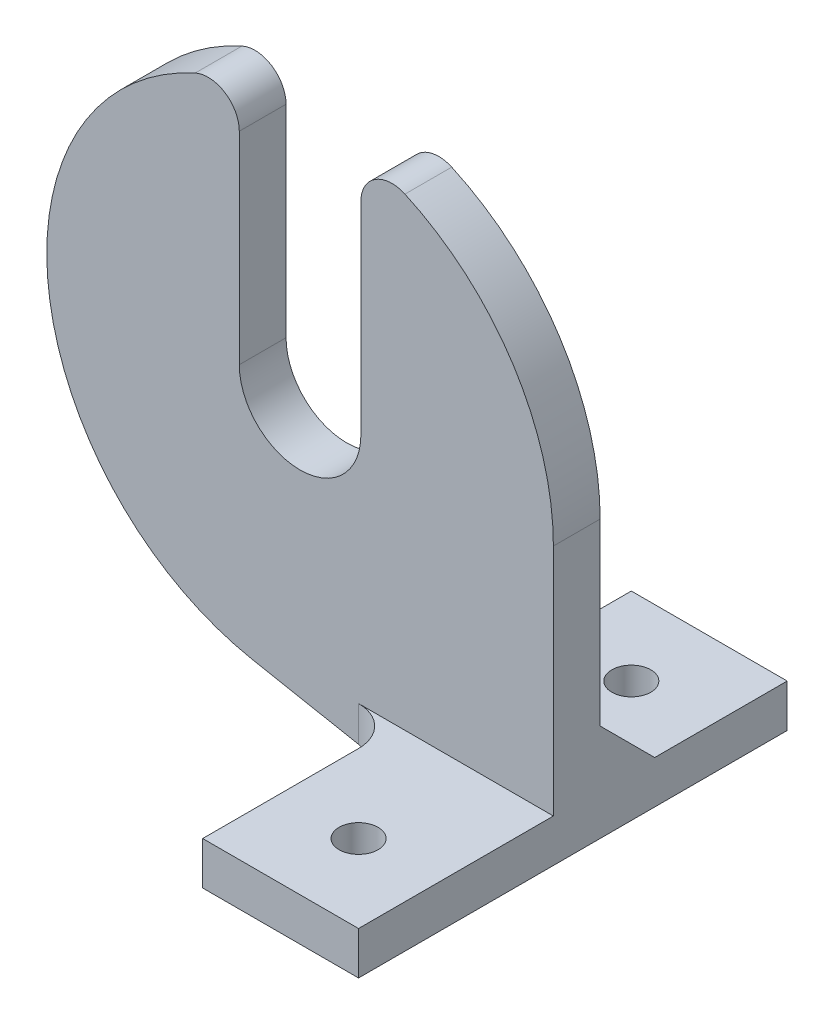
SolidWorks part; units mm, degrees
ref_plane "Front Plane" through (0, 0, 0) normal (0, 0, 1) x (1, 0, 0)
ref_plane "Top Plane" through (0, 0, 0) normal (0, 1, 0) x (1, 0, 0)
ref_plane "Right Plane" through (0, 0, 0) normal (1, 0, 0) x (0, 0, -1)
sketch "Sketch1" plane through (0, 0, 0) normal (0, 0, 1) x (1, 0, 0)
  line L0 (41.275, -41.275) -> (0, -41.275)
  line L1 (41.275, 0) -> (41.275, -41.275)
  line L2 (-9.906, 0) -> (-9.906, 40.0687)
  line L3 (9.906, 0) -> (9.906, 40.0687)
  circle A0 centre (0, 0) radius 9.906 construction
  arc A1 (41.275, 0) -> (9.906, 40.0687) centre (0, 0) ccw
  arc A2 (-9.906, 40.0687) -> (0, -41.275) centre (0, 0) ccw
  arc A3 (9.906, 0) -> (-9.906, 0) centre (0, 0) cw
  circle A4 centre (0, 0) radius 38.1 construction
  dimension "D1" = 19.812
  dimension "D2" = 82.55
  dimension "D3" = 76.2
  dimension "D4" = 3.175
extrude "Boss-Extrude1" add sketch "Sketch1" along normal blind 7.62
sketch "Sketch2" plane through (0, 0, 7.62) normal (0, 0, 1) x (1, 0, 0)
  line L0 (41.275, -41.275) -> (41.275, 0) construction
  line L5 (41.275, -38.1) -> (15.875, -38.1)
  line L6 (41.275, -38.1) -> (41.275, -45.085)
  line L7 (41.275, -45.085) -> (15.875, -45.085)
  line L8 (15.875, -38.1) -> (15.875, -45.085)
  line L9 (0, -41.275) -> (41.275, -41.275) construction
  dimension "D1" = 25.4
  dimension "D2" = 3.175
  dimension "D3" = 3.81
extrude "Boss-Extrude2" add sketch "Sketch2" along normal blind 31.75 and the other way blind 38.1
sketch "Sketch3" plane through (0, 0, 7.62) normal (0, 0, 1) x (1, 0, 0)
  line L0 (15.875, -45.085) -> (-7.796, -40.5321)
  line L1 (15.875, -41.275) -> (15.875, -45.085)
  line L7 (0, -41.275) -> (15.875, -41.275)
  line L8 (15.875, -41.275) -> (15.875, -38.1)
  line L9 (15.875, -38.1) -> (41.275, -38.1)
  line L10 (41.275, -38.1) -> (41.275, 0)
  line L11 (9.906, 40.0687) -> (9.906, 0)
  line L12 (-9.906, 0) -> (-9.906, 40.0687)
  line L13 (0, -41.275) -> (15.875, -41.275)
  arc A0 (-9.906, 40.0687) -> (0, -41.275) centre (0, 0) ccw construction
  arc A4 (41.275, 0) -> (9.906, 40.0687) centre (0, 0) ccw
  arc A5 (-9.906, 0) -> (9.906, 0) centre (0, 0) ccw
  arc A6 (-9.906, 40.0687) -> (0, -41.275) centre (0, 0) ccw
  arc A9 (-7.796, -40.5321) -> (0, -41.275) centre (0, 0) ccw
  dimension "D1" = 0
extrude "Boss-Extrude3" add sketch "Sketch3" against normal blind 7.62
sketch "Sketch4" plane through (0, -38.1, 0) normal (0, 1, 0) x (1, 0, 0)
  line L0 (41.275, -39.37) -> (15.875, -39.37) construction
  line L1 (15.875, -7.62) -> (15.875, -39.37) construction
  line L2 (15.875, 30.48) -> (15.875, 0) construction
  line L3 (41.275, 30.48) -> (15.875, 30.48) construction
  circle A0 centre (28.575, -26.67) radius 3.175
  circle A1 centre (28.575, 17.78) radius 3.175
  dimension "D1" = 6.35
  dimension "D4" = 6.35
  dimension "D2" = 12.7
  dimension "D3" = 12.7
  dimension "D5" = 12.7
  dimension "D6" = 12.7
extrude "Cut-Extrude1" cut sketch "Sketch4" against normal blind 7.62
chamfer "Chamfer1" distance 8.89 angle 45 1 edges at (28.575, -38.1, 0)
fillet "Fillet1" radius 6.35 2 edges at (15.875, -41.5925, 7.62) (15.875, -37.1475, 0)
fillet "Fillet2" radius 5.08 2 edges at (9.906, 40.0687, 3.81) (-9.906, 40.0687, 3.81)
sketch "Sketch5" plane through (0, 0, 0) normal (0, 0, -1) x (-1, 0, 0)
  circle A0 centre (0, 0) radius 37.5
  dimension "D1" = 75
